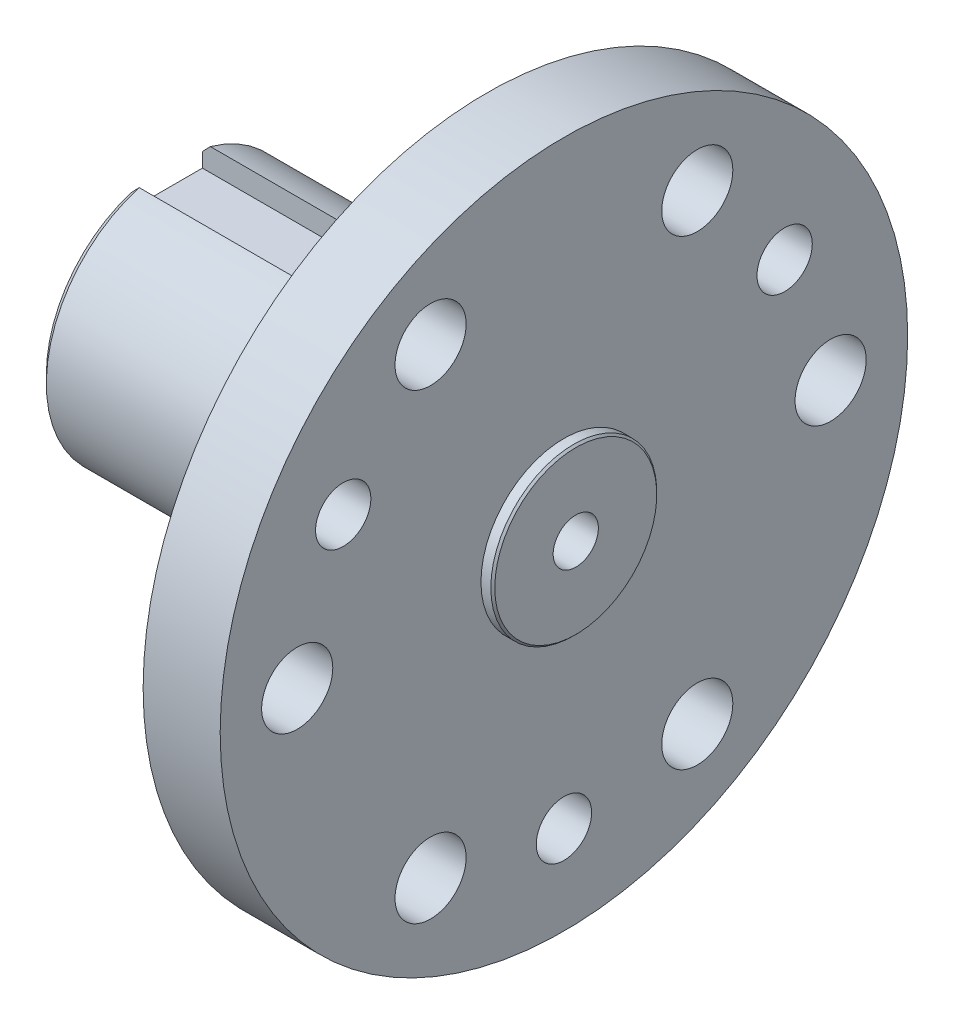
SolidWorks part; units mm, degrees
ref_plane "正面" through (0, 0, 0) normal (0, 0, 1) x (1, 0, 0)
ref_plane "平面" through (0, 0, 0) normal (0, 1, 0) x (1, 0, 0)
ref_plane "右側面" through (0, 0, 0) normal (1, 0, 0) x (0, 0, -1)
sketch "ｽｹｯﾁ1" plane through (0, 0, 0) normal (0, 0, 1) x (1, 0, 0)
  line L0 (0, 0) -> (0, 32.5)
  line L1 (0, 32.5) -> (81, 32.5)
  line L2 (81, 32.5) -> (81, 87)
  line L3 (81, 87) -> (100.5, 87)
  line L4 (100.5, 87) -> (100.5, 21)
  line L5 (100.5, 21) -> (103.5, 21)
  line L6 (103.5, 21) -> (103.5, 0)
  line L7 (103.5, 0) -> (0, 0)
  line L8 (0, 0) -> (103.5, 0) construction
revolve "回転1" add sketch "ｽｹｯﾁ1" angle 360 about L8
fillet "ﾌｨﾚｯﾄ1" radius 2 1 edges at (81, 0, 32.5)
chamfer "面取り1" distance 2 angle 45 1 edges at (0, 0, 32.5)
chamfer "面取り2" distance 0.5 angle 45 1 edges at (103.5, 0, 21)
sketch "ｽｹｯﾁ2" plane through (0, 0, 0) normal (1, 0, 0) x (0, 0, -1)
  circle A0 centre (0, 0) radius 15
sketch "ｽｹｯﾁ3" plane through (0, 0, 0) normal (1, 0, 0) x (0, 0, -1)
  circle A0 centre (0, 0) radius 15
sketch "ｽｹｯﾁ4" plane through (0, 0, 0) normal (1, 0, 0) x (0, 0, -1)
  circle A0 centre (0, 0) radius 15
extrude "ｶｯﾄ - 押し出し3" cut sketch "ｽｹｯﾁ4" along normal blind 20
chamfer "面取り3" distance 3 angle 45 1 edges at (0, 0, -15)
sketch "ｽｹｯﾁ5" plane through (0, 0, 0) normal (1, 0, 0) x (0, 0, -1)
  circle A0 centre (0, 0) radius 5.7226
extrude "ｶｯﾄ - 押し出し4" cut sketch "ｽｹｯﾁ5" against normal through all and the other way through all
ref_plane "平面1" through (0, 40, 0) normal (0, 1, 0) x (1, 0, 0)
sketch "ｽｹｯﾁ6" plane through (0, 40, 0) normal (0, 1, 0) x (1, 0, 0)
  line L0 (-5, 0) -> (57, 0) construction
  line L1 (-5, 9) -> (57, 9)
  line L2 (-5, -9) -> (57, -9)
  arc A0 (-5, 9) -> (-5, -9) centre (-5, 0) ccw
  arc A1 (57, -9) -> (57, 9) centre (57, 0) ccw
  point P3 (26, 0)
  point P8 (0, 0)
extrude "ｶｯﾄ - 押し出し5" cut sketch "ｽｹｯﾁ6" against normal blind 14.5
sketch "ｽｹｯﾁ7" plane through (0, 0, 0) normal (1, 0, 0) x (0, 0, -1)
  circle A0 centre (67.5, 0) radius 9
  circle A1 centre (33.75, 58.4567) radius 9
  circle A2 centre (-33.75, 58.4567) radius 9
  circle A3 centre (-67.5, 0) radius 9
  circle A4 centre (-33.75, -58.4567) radius 9
  circle A5 centre (33.75, -58.4567) radius 9
  circle A6 centre (55.8586, 32.25) radius 7
  circle A7 centre (-55.8586, 32.25) radius 7
  circle A8 centre (0, -64.5) radius 7
extrude "ｶｯﾄ - 押し出し6" cut sketch "ｽｹｯﾁ7" against normal through all and the other way through all
